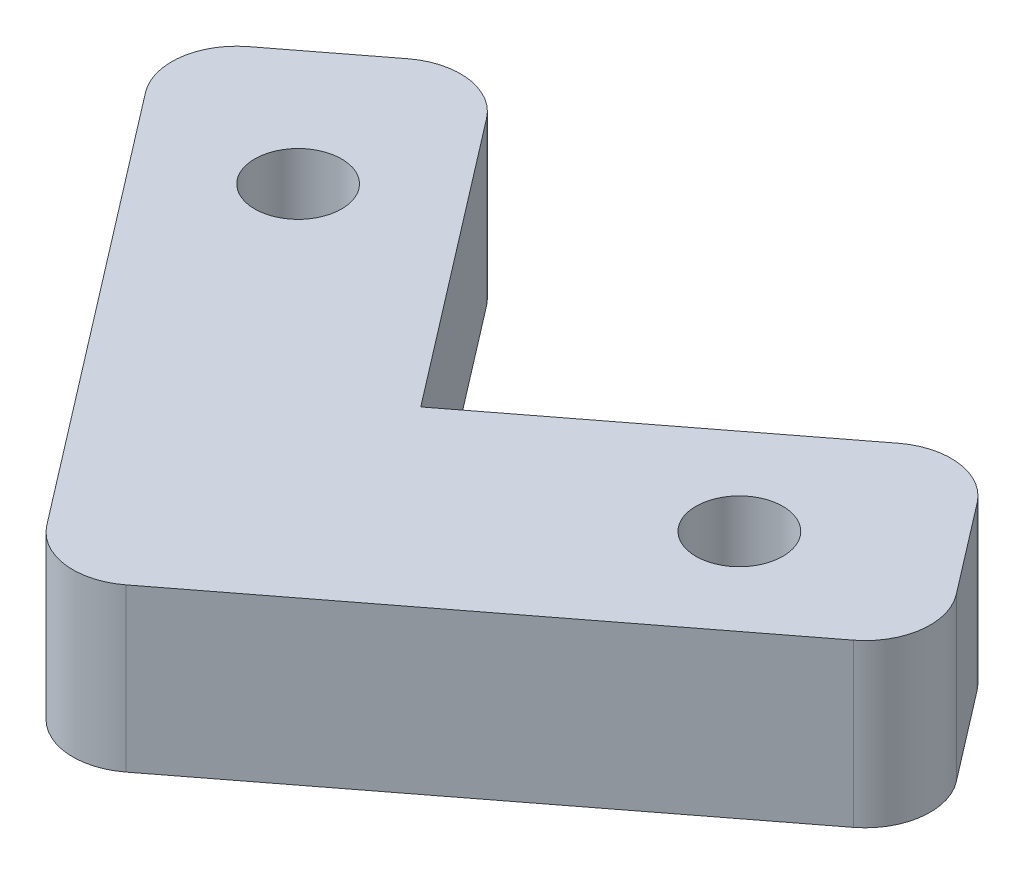
SolidWorks part; units mm, degrees
ref_plane "Front Plane" through (0, 0, 0) normal (0, 0, 1) x (1, 0, 0)
ref_plane "Top Plane" through (0, 0, 0) normal (0, 1, 0) x (1, 0, 0)
ref_plane "Right Plane" through (0, 0, 0) normal (1, 0, 0) x (0, 0, -1)
sketch "Sketch1" plane through (0, 0, 0) normal (0, 1, 0) x (1, 0, 0)
  line L0 (0, 0) -> (0, -152.4) construction
  line L1 (-152.4, -152.4) -> (152.4, -152.4) construction
  line L2 (-152.4, -152.4) -> (-152.4, 152.4) construction
  line L3 (-152.4, 152.4) -> (152.4, 152.4) construction
  line L4 (152.4, -152.4) -> (152.4, 152.4) construction
  line L5 (-152.4, -152.4) -> (152.4, 152.4) construction
  line L6 (-152.4, 152.4) -> (152.4, -152.4) construction
  line L7 (0, 0) -> (0, 102.2502) construction
  line L8 (0, 102.2502) -> (65.7158, 16.6077) construction
  line L9 (143.0285, -84.1481) -> (65.7158, 16.6077) construction
  line L10 (50.6024, 5.0108) -> (80.8292, 28.2047) construction
  line L11 (50.6024, 5.0108) -> (127.9151, -95.745) construction
  line L12 (127.9151, -95.745) -> (158.1419, -72.5512) construction
  line L13 (80.8292, 28.2047) -> (158.1419, -72.5512) construction
  line L14 (0, 102.2502) -> (50.1691, -133.7768) construction
  line L15 (50.1691, -133.7768) -> (68.8028, -129.8161) construction
  line L16 (68.8028, -129.8161) -> (42.398, -5.5913) construction
  line L17 (42.398, -5.5913) -> (5.1306, -13.5127) construction
  line L18 (5.1306, -13.5127) -> (31.5354, -137.7375) construction
  line L19 (31.5354, -137.7375) -> (50.1691, -133.7768) construction
  line L20 (0, 102.2502) -> (-65.7158, 16.6077) construction
  line L21 (-50.6024, 5.0108) -> (-80.8292, 28.2047) construction
  line L22 (-127.9151, -95.745) -> (-158.1419, -72.5512) construction
  line L23 (-80.8292, 28.2047) -> (-158.1419, -72.5512) construction
  line L24 (-50.6024, 5.0108) -> (-127.9151, -95.745) construction
  line L25 (-143.0285, -84.1481) -> (-65.7158, 16.6077) construction
  line L26 (-31.5354, -137.7375) -> (-50.1691, -133.7768) construction
  line L27 (-50.1691, -133.7768) -> (-68.8028, -129.8161) construction
  line L28 (-42.398, -5.5913) -> (-5.1306, -13.5127) construction
  line L29 (-5.1306, -13.5127) -> (-31.5354, -137.7375) construction
  line L30 (0, 102.2502) -> (-50.1691, -133.7768) construction
  line L31 (-68.8028, -129.8161) -> (-42.398, -5.5913) construction
  line L32 (0, 102.2502) -> (-152.4, -101.762) construction
  line L33 (0, 102.2502) -> (-112.0468, 18.8141) construction
  line L34 (0, 102.2502) -> (112.0468, 18.8141) construction
  line L35 (-105.9774, 26.7239) -> (-94.0975, 42.206) construction
  line L36 (94.0975, 42.206) -> (105.9774, 26.7239) construction
  line L37 (0, 102.2502) -> (152.4, -101.762) construction
  line L38 (-152.4, -50.962) -> (-152.4, -101.762) construction
  line L39 (152.4, -50.962) -> (152.4, -101.762) construction
  line L40 (72.5295, -129.0239) -> (45.3326, -1.0724) construction
  line L41 (45.3326, -1.0724) -> (0.6117, -10.5781) construction
  line L42 (0.6117, -10.5781) -> (27.8086, -138.5296) construction
  line L43 (81.5325, 33.5467) -> (161.1646, -70.2318) construction
  line L44 (45.2604, 5.7141) -> (81.5325, 33.5467) construction
  line L45 (45.2604, 5.7141) -> (124.8924, -98.0644) construction
  line L46 (98.1127, 11.939) -> (81.5325, 33.5467) construction
  line L47 (81.5325, 33.5467) -> (63.3964, 19.6304) construction
  line L48 (63.3964, 19.6304) -> (57.9845, 26.6833) construction
  line L49 (100.7298, 33.5626) -> (94.0975, 42.206) construction
  line L50 (91.0399, 21.1564) -> (81.5325, 33.5467) construction
  line L51 (81.5325, 33.5467) -> (63.3964, 19.6304) construction
  line L52 (54.7678, -6.6762) -> (45.2604, 5.7141) construction
  line L53 (45.2604, 5.7141) -> (63.3964, 19.6304) construction
  line L54 (47.2595, -10.1376) -> (45.3326, -1.0724) construction
  line L55 (45.3326, -1.0724) -> (0.6117, -10.5781) construction
  line L56 (-0.6117, -10.5781) -> (0.6117, -10.5781) construction
  line L57 (-100.7298, 33.5626) -> (-94.0975, 42.206) construction
  line L58 (-91.0399, 21.1564) -> (-81.5325, 33.5467) construction
  line L59 (-81.5325, 33.5467) -> (-63.3964, 19.6304) construction
  line L60 (-45.2604, 5.7141) -> (-63.3964, 19.6304) construction
  line L61 (-54.7678, -6.6762) -> (-45.2604, 5.7141) construction
  line L62 (-47.2595, -10.1376) -> (-45.3326, -1.0724) construction
  line L63 (-45.3326, -1.0724) -> (-0.6117, -10.5781) construction
  line L64 (-152.4, -78.9511) -> (-152.4, -95.2943) construction
  line L65 (152.4, -78.9511) -> (152.4, -95.2943) construction
  line L66 (47.5797, 2.6915) -> (127.2118, -101.0871) construction
  line L67 (127.2118, -101.0871) -> (160.4613, -75.5739) construction
  line L68 (125.4536, -114.4422) -> (145.6048, -98.9797)
  line L69 (145.6048, -98.9797) -> (139.8063, -91.423)
  line L70 (125.4536, -114.4422) -> (109.6045, -93.7873)
  line L71 (109.6045, -93.7873) -> (117.1612, -87.9888)
  line L72 (117.1612, -87.9888) -> (127.2118, -101.0871)
  line L73 (139.8063, -91.423) -> (127.2118, -101.0871)
  line L74 (127.9151, -95.745) -> (127.2118, -101.0871) construction
  line L75 (57.1725, -136.1833) -> (73.3217, -132.7507) construction
  line L76 (79.2059, -114.6211) -> (69.8891, -116.6014) construction
  line L77 (68.8028, -129.8161) -> (73.3217, -132.7507) construction
  line L78 (69.8891, -116.6014) -> (73.3217, -132.7507) construction
  line L79 (59.0208, -144.879) -> (57.1725, -136.1833) construction
  line L80 (84.4869, -139.466) -> (79.2059, -114.6211) construction
  line L81 (84.4869, -139.466) -> (59.0208, -144.879) construction
  circle A0 centre (0, 102.2502) radius 12.7 construction
  arc A1 (-147.0329, -105.6634) -> (147.0329, -105.6634) centre (0, 102.2502) ccw construction
  arc A2 (-131.9457, -68.8932) -> (131.9457, -68.8932) centre (0, 102.2502) ccw construction
  arc A3 (-105.492, 10.6668) -> (105.492, 10.6668) centre (0, 102.2502) ccw construction
  arc A4 (-74.137, 42.4484) -> (74.137, 42.4484) centre (0, 102.2502) ccw construction
  arc A5 (74.137, 42.4484) -> (94.0975, 42.206) centre (84.0219, 34.4748) cw construction
  arc A6 (-74.137, 42.4484) -> (-94.0975, 42.206) centre (-84.0219, 34.4748) ccw construction
  arc A7 (105.9774, 26.7239) -> (105.492, 10.6668) centre (95.9018, 18.9926) cw construction
  arc A8 (-105.9774, 26.7239) -> (-105.492, 10.6668) centre (-95.9018, 18.9926) ccw construction
  arc A9 (-97.8072, 11.6082) -> (110.1733, 27.1232) centre (0, 102.2502) ccw construction
  circle A10 centre (102.87, 17.3975) radius 1.7005 construction
  circle A11 centre (83.82, 40.64) radius 1.7005 construction
  circle A12 centre (25.4, 2.54) radius 1.7005 construction
  circle A13 centre (0, -30.48) radius 1.7005 construction
  circle A14 centre (-102.87, 17.3975) radius 1.7005 construction
  circle A15 centre (-83.82, 40.64) radius 1.7005 construction
  circle A16 centre (-25.4, 2.54) radius 1.7005 construction
  arc A17 (74.137, 42.4484) -> (-74.137, 42.4484) centre (0, 102.2502) cw construction
  arc A18 (-89.4237, 19.3775) -> (100.7298, 33.5626) centre (0, 102.2502) ccw construction
  arc A19 (91.0399, 21.1564) -> (100.7298, 33.5626) centre (0, 102.2502) ccw construction
  arc A20 (94.0975, 42.206) -> (74.137, 42.4484) centre (84.0219, 34.4748) ccw construction
  arc A21 (54.7678, -6.6762) -> (47.2595, -10.1376) centre (0, 102.2502) cw construction
  circle A22 centre (0, 0) radius 1.7005 construction
  circle A23 centre (-83.82, 40.64) radius 1.7005 construction
  arc A24 (-94.0975, 42.206) -> (-74.137, 42.4484) centre (-84.0219, 34.4748) cw construction
  arc A25 (-91.0399, 21.1564) -> (-100.7298, 33.5626) centre (0, 102.2502) cw construction
  arc A26 (-54.7678, -6.6762) -> (-47.2595, -10.1376) centre (0, 102.2502) ccw construction
  arc A27 (131.9457, -68.8932) -> (152.4, -78.9511) centre (139.7, -78.9511) cw construction
  arc A28 (152.4, -95.2943) -> (147.0329, -105.6634) centre (139.7, -95.2943) cw construction
  arc A29 (-147.0329, -105.6634) -> (-152.4, -95.2943) centre (-139.7, -95.2943) cw construction
  arc A30 (-131.9457, -68.8932) -> (-152.4, -78.9511) centre (-139.7, -78.9511) ccw construction
  circle A31 centre (117.2485, -95.9258) radius 1.7005
  circle A32 centre (137.6677, -99.067) radius 1.7005
  circle A33 centre (75.8677, -121.8225) radius 1.7005 construction
  circle A34 centre (64.3739, -139.5215) radius 1.7005 construction
  point P0 (0, 0)
  point P60 (98.1127, 11.939)
  dimension "D4" = 25.4
  dimension "D19" = 12.7
  dimension "D13" = 139.7
  dimension "D14" = 95.25
  dimension "D18" = 12.7
  dimension "D21" = 133.35
  dimension "D22" = 3.4011
  dimension "D28" = 30.48
  dimension "D31" = 12.7
  dimension "D17" = 3.4011
  dimension "D38" = 3.4011
  dimension "D1" = 304.8
  dimension "D2" = 304.8
  dimension "D3" = 50.1498
  dimension "D5" = 127
  dimension "D6" = 38.1
  dimension "D7" = 37.5
  dimension "D8" = 107.95
  dimension "D9" = 12
  dimension "D10" = 38.1
  dimension "D11" = 127
  dimension "D12" = 114.3
  dimension "D15" = 19.05
  dimension "D16" = 50.8
  dimension "D20" = 3.81
  dimension "D23" = 102.87
  dimension "D24" = 83.82
  dimension "D25" = 40.64
  dimension "D26" = 25.4
  dimension "D27" = 2.54
  dimension "D30" = 11.8077
  dimension "D33" = 9.525
  dimension "D34" = 9.525
  dimension "D35" = 3.81
  dimension "D36" = 25.4
  dimension "D37" = 12.7
  dimension "D39" = 6.35
  dimension "D40" = 6.35
  dimension "D41" = 4.7625
  dimension "D42" = 4.7625
  dimension "D43" = 3.81
  dimension "D44" = 12.7
  dimension "D45" = 12.7
  dimension "D46" = 9.525
  dimension "D47" = 4.7625
  dimension "D48" = 6.35
  dimension "D49" = 6.35
  dimension "D50" = 4.7625
  dimension "D51" = 25.4
  dimension "D29" = 11.43
  dimension "D32" = 3.81
extrude "Boss-Extrude1" add sketch "Sketch1" along normal blind 6.35
fillet "Fillet1" radius 2.54 5 edges at (139.8063, 3.175, 91.423) (117.1612, 3.175, 87.9888) (145.6048, 3.175, 98.9797) (109.6045, 3.175, 93.7873) (125.4536, 3.175, 114.4422)
